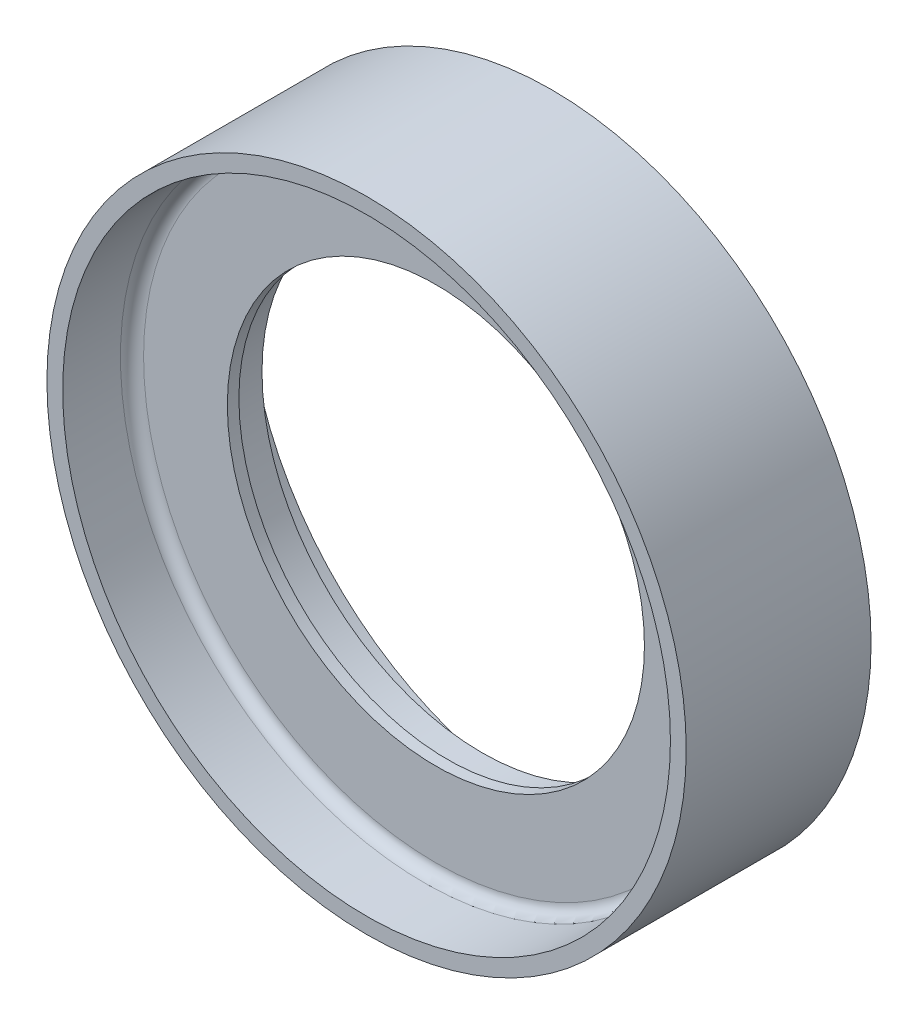
SolidWorks part; units mm, degrees
ref_plane "Front Plane" through (0, 0, 0) normal (0, 0, 1) x (1, 0, 0)
ref_plane "Top Plane" through (0, 0, 0) normal (0, 1, 0) x (1, 0, 0)
ref_plane "Right Plane" through (0, 0, 0) normal (1, 0, 0) x (0, 0, -1)
sketch "Sketch1" plane through (0, 0, 0) normal (0, 0, 1) x (1, 0, 0)
  circle A4 centre (0, 0) radius 13.8327
  circle A5 centre (0, 0) radius 13.15
  circle A6 centre (0, 0) radius 13.15
  dimension "D1" = 0.15
  dimension "D3" = 0.6827
  dimension "D2" = 27.6654
extrude "Boss-Extrude1" add sketch "Sketch1" against normal blind 3
sketch "Sketch2" plane through (0, 0, 0) normal (0, 0, 1) x (1, 0, 0)
  circle A0 centre (0, 0) radius 13.8327
  circle A1 centre (0, 0) radius 9.025
  dimension "D1" = 18.05
extrude "Boss-Extrude2" add sketch "Sketch2" along normal blind 2
sketch "Sketch3" plane through (0, 0, 2) normal (0, 0, 1) x (1, 0, 0)
  circle A0 centre (0, 0) radius 13.15 construction
  circle A1 centre (0, 0) radius 13.8327
  circle A2 centre (0, 0) radius 13.8327
  circle A3 centre (0, 0) radius 13.15
  dimension "D1" = 0
extrude "Boss-Extrude3" add sketch "Sketch3" along normal blind 3
fillet "Fillet1" radius 0.5 2 edges at (13.15, 0, 2) (13.15, 0, 0)
sketch "Sketch4" plane through (0, 0, 0) normal (0, 0, -1) x (-1, 0, 0)
  circle A1 centre (0, 0) radius 9.525
extrude "Cut-Extrude2" cut sketch "Sketch4" against normal blind 1.5
